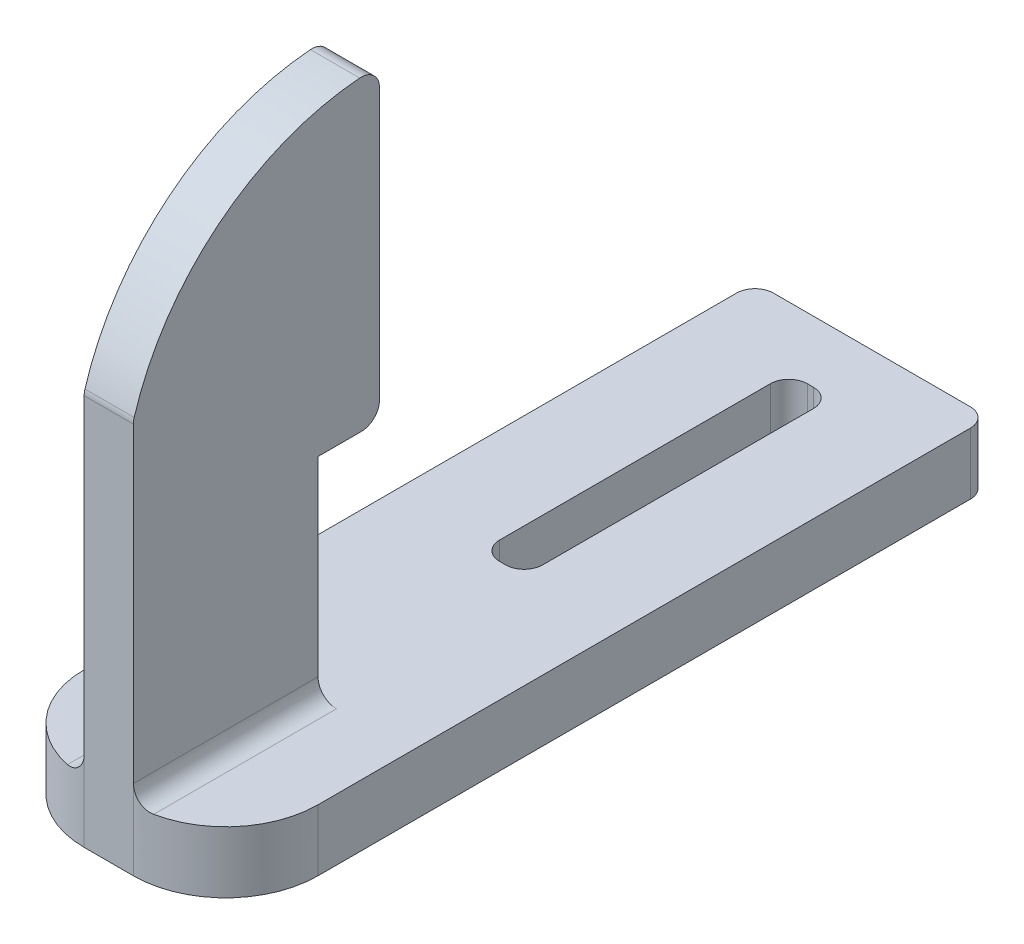
SolidWorks part; units mm, degrees
ref_plane "Front Plane" through (0, 0, 0) normal (0, 0, 1) x (1, 0, 0)
ref_plane "Top Plane" through (0, 0, 0) normal (0, 1, 0) x (1, 0, 0)
ref_plane "Right Plane" through (0, 0, 0) normal (1, 0, 0) x (0, 0, -1)
sketch "Sketch1" plane through (0, 0, 0) normal (0, 1, 0) x (1, 0, 0)
  line L1 (0, 0) -> (-19, 0)
  line L2 (0, 0) -> (0, 62)
  line L3 (0, 62) -> (-19, 62)
  line L4 (-19, 0) -> (-19, 62)
  line L5 (-11.25, 57) -> (-7.75, 57)
  line L6 (-11.25, 57) -> (-11.25, 32)
  line L7 (-11.25, 32) -> (-7.75, 32)
  line L8 (-7.75, 57) -> (-7.75, 32)
  point P9 (-9.5, 57)
  point P10 (-9.5, 62)
  dimension "D1" = 62
  dimension "D2" = 19
  dimension "D3" = 3.5
  dimension "D4" = 5
  dimension "D5" = 25
extrude "Boss-Extrude1" add sketch "Sketch1" along normal blind 5
sketch "Sketch4" plane through (0, 5, 0) normal (0, 1, 0) x (1, 0, 0)
  line L0 (0, 62) -> (-19, 62) construction
  line L1 (-11.5, 15) -> (-7.5, 15)
  line L2 (-11.5, 15) -> (-11.5, 0)
  line L3 (-11.5, 0) -> (-7.5, 0)
  line L4 (-7.5, 15) -> (-7.5, 0)
  line L5 (0, 62) -> (-19, 62) construction
  point P6 (-9.5, 62)
  point P7 (-9.5, 15)
  dimension "D1" = 4
  dimension "D2" = 15
  dimension "D3" = 47
extrude "Boss-Extrude3" add sketch "Sketch4" along normal blind 17
sketch "Sketch5" plane through (-7.5, 0, 0) normal (1, 0, 0) x (0, 0, -1)
  line L0 (15, 22) -> (20, 22)
  line L1 (20, 22) -> (20, 47)
  line L2 (20, 47) -> (78.519, 47) construction
  line L3 (0, 22) -> (15, 22)
  line L4 (0, 22) -> (0, 32)
  arc A1 (0, 32) -> (20, 47) centre (20, 26.1667) cw
  dimension "D1" = 5
  dimension "D2" = 25
  dimension "D3" = 10
extrude "Boss-Extrude4" add sketch "Sketch5" against normal blind 4
sketch "Sketch6" plane through (0, 5, 0) normal (0, 1, 0) x (1, 0, 0)
  line L3 (-11.5, 15) -> (-11.5, 0) construction
  line L8 (-19, 0) -> (-11.5, 0) construction
  line L9 (-19, 7.5) -> (-19, 0)
  line L10 (-19, 0) -> (-11.5, 0)
  line L11 (-9.5, 0) -> (-9.5, 20) construction
  line L12 (-11.5, 0) -> (-7.5, 0) construction
  line L13 (-11.5, 20) -> (-7.5, 20) construction
  line L14 (0, 0) -> (-7.5, 0)
  line L15 (0, 7.5) -> (0, 0)
  arc A2 (-19, 7.5) -> (-11.5, 0) centre (-11.5, 7.5) ccw
  arc A3 (0, 7.5) -> (-7.5, 0) centre (-7.5, 7.5) cw
  dimension "D1" = 7.5
extrude "Cut-Extrude1" cut sketch "Sketch6" against normal through all
fillet "Fillet1" radius 1.5 11 edges at (-9.5, 22, -20) (-11.25, 2.5, -57) (-7.75, 2.5, -57) (-7.75, 2.5, -32) (-11.25, 2.5, -32) (-19, 2.5, -62) (0, 2.5, -62) (-11.5, 5, -7.5) (-7.5, 5, -7.5) (-9.5, 47, -20) (-9.5, 32, 0)
